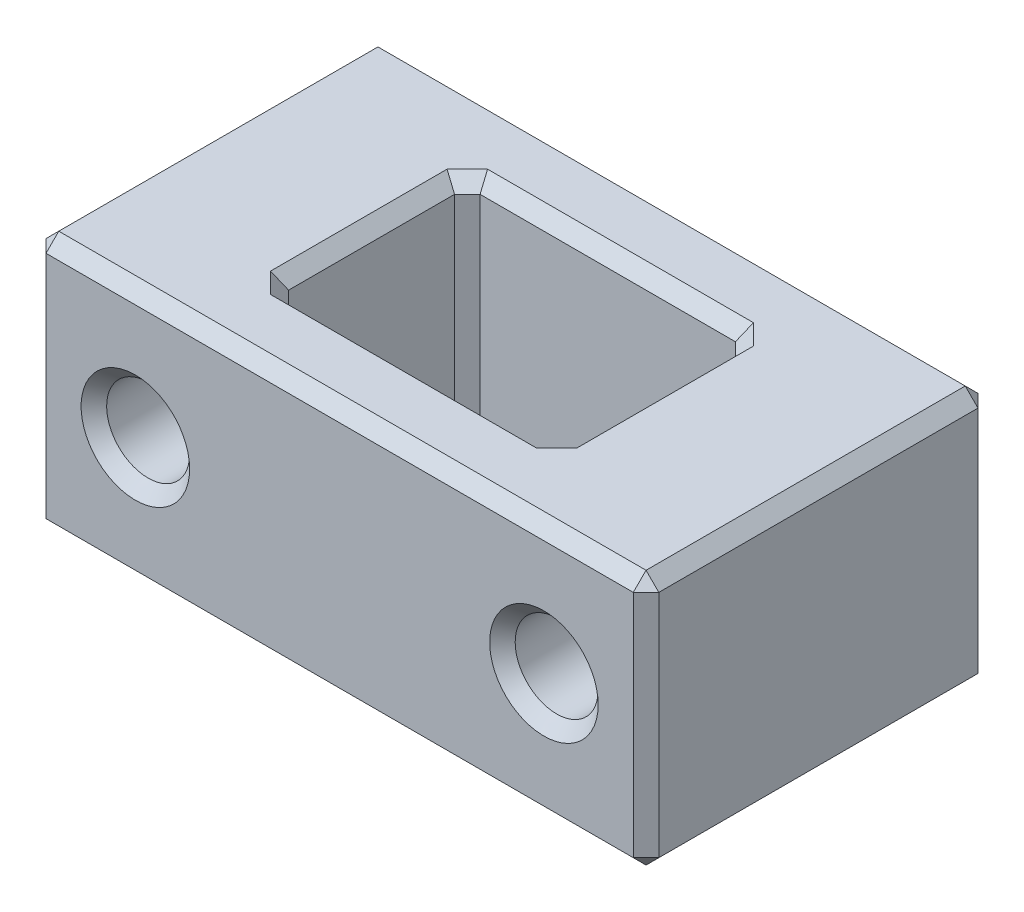
SolidWorks part; units mm, degrees
ref_plane "Front Plane" through (0, 0, 0) normal (0, 0, 1) x (1, 0, 0)
ref_plane "Top Plane" through (0, 0, 0) normal (0, 1, 0) x (1, 0, 0)
ref_plane "Right Plane" through (0, 0, 0) normal (1, 0, 0) x (0, 0, -1)
ref_plane "Plane1" through (0, 9.5089, 0) normal (0, -1, 0) x (1, 0, 0)
sketch "Sketch1" plane through (0, 9.5089, 0) normal (0, -1, 0) x (1, 0, 0)
  line L0 (-102.3057, 0) -> (-54.3057, 0)
  line L1 (-54.3057, 0) -> (-54.3057, 27)
  line L2 (-54.3057, 27) -> (-102.3057, 27)
  line L3 (-102.3057, 27) -> (-102.3057, 0)
  dimension "D1" = 48
  dimension "D2" = 27
extrude "Boss-Extrude1" add sketch "Sketch1" against normal blind 20
sketch "Sketch2" plane through (0, 9.5089, 0) normal (0, -1, 0) x (1, 0, 0)
  line L0 (-67.3057, 6) -> (-67.3057, 21)
  line L1 (-67.3057, 21) -> (-89.3057, 21)
  line L2 (-89.3057, 21) -> (-89.3057, 6)
  line L3 (-89.3057, 6) -> (-67.3057, 6)
  line L4 (-78.3057, 27) -> (-78.3057, 0) construction
  line L5 (-54.3057, 27) -> (-102.3057, 27) construction
  line L6 (-102.3057, 0) -> (-54.3057, 0) construction
  line L7 (-102.3057, 13.5) -> (-54.3057, 13.5) construction
  line L8 (-102.3057, 27) -> (-102.3057, 0) construction
  line L9 (-54.3057, 0) -> (-54.3057, 27) construction
  dimension "D2" = 15
  dimension "D3" = 22
extrude "Cut-Extrude1" cut sketch "Sketch2" against normal through all
sketch "Sketch11" plane through (0, 0, 0) normal (0, 0, -1) x (-1, 0, 0)
  line L0 (94.3057, 19.5089) -> (62.3057, 19.5089) construction
  line L1 (78.3057, 9.5089) -> (78.3057, 29.5089) construction
  line L2 (102.3057, 9.5089) -> (54.3057, 9.5089) construction
  line L3 (102.3057, 29.5089) -> (54.3057, 29.5089) construction
  circle A0 centre (94.3057, 19.5089) radius 3.25
  circle A1 centre (62.3057, 19.5089) radius 3.25
  dimension "D1" = 6.5
  dimension "D2" = 10
  dimension "D3" = 32
extrude "Cut-Extrude2" cut sketch "Sketch11" against normal through all
chamfer "Chamfer2" distance 1 angle 45 4 edges at (-89.3057, 19.5089, 6) (-67.3057, 19.5089, 6) (-67.3057, 19.5089, 21) (-89.3057, 19.5089, 21)
chamfer "Chamfer1" distance 1 angle 45 32 edges at (-88.8057, 29.5089, 6.5) (-89.3057, 29.5089, 13.5) (-88.8057, 29.5089, 20.5) (-78.3057, 29.5089, 21) (-67.8057, 29.5089, 20.5) (-67.3057, 29.5089, 13.5) (-67.8057, 29.5089, 6.5) (-78.3057, 29.5089, 6) (-67.3057, 9.5089, 13.5) (-67.8057, 9.5089, 20.5) (-78.3057, 9.5089, 21) (-88.8057, 9.5089, 20.5) (-89.3057, 9.5089, 13.5) (-88.8057, 9.5089, 6.5) (-78.3057, 9.5089, 6) (-67.8057, 9.5089, 6.5) (-97.5557, 19.5089, 27) (-65.5557, 19.5089, 27) (-97.5557, 19.5089, 0) (-65.5557, 19.5089, 0) (-78.3057, 29.5089, 27) (-78.3057, 9.5089, 27) (-54.3057, 19.5089, 27) (-54.3057, 29.5089, 13.5) (-54.3057, 9.5089, 13.5) (-54.3057, 19.5089, 0) (-78.3057, 29.5089, 0) (-78.3057, 9.5089, 0) (-102.3057, 19.5089, 0) (-102.3057, 29.5089, 13.5) (-102.3057, 19.5089, 27) (-102.3057, 9.5089, 13.5)
